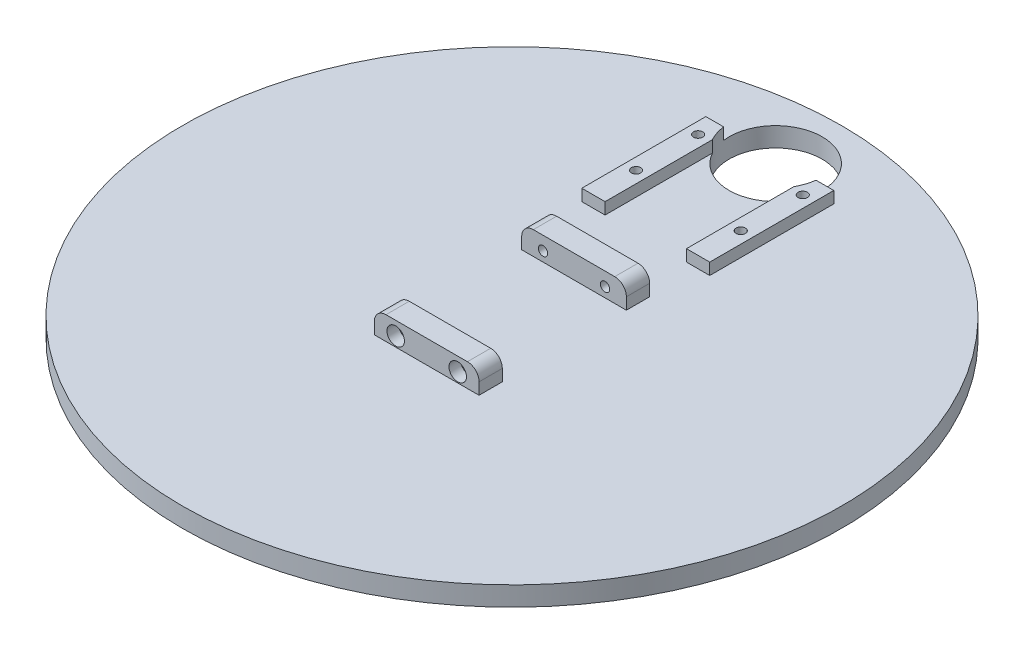
SolidWorks part; units mm, degrees
ref_plane "Front Plane" through (0, 0, 0) normal (0, 0, 1) x (1, 0, 0)
ref_plane "Top Plane" through (0, 0, 0) normal (0, 1, 0) x (1, 0, 0)
ref_plane "Right Plane" through (0, 0, 0) normal (1, 0, 0) x (0, 0, -1)
sketch "Sketch1" plane through (0, 0, 0) normal (0, 1, 0) x (1, 0, 0)
  circle A0 centre (0, 0) radius 32.65
  circle A1 centre (0, 0) radius 37.65
  dimension "D1" = 65.3
  dimension "D2" = 5
extrude "Boss-Extrude1" add sketch "Sketch1" along normal blind 10
sketch "Sketch2" plane through (0, 10, 0) normal (0, 1, 0) x (1, 0, 0)
  circle A0 centre (0, 0) radius 29.65
  circle A1 centre (0, 0) radius 32.65 construction
  circle A2 centre (0, 0) radius 32.65
  dimension "D1" = 3
extrude "Boss-Extrude2" add sketch "Sketch2" against normal blind 4
sketch "Sketch3" plane through (0, 10, 0) normal (0, 1, 0) x (1, 0, 0)
  circle A0 centre (0, 0) radius 85
  dimension "D1" = 170
extrude "Boss-Extrude3" add sketch "Sketch3" along normal blind 5
sketch "Sketch4" plane through (0, 15, 0) normal (0, 1, 0) x (1, 0, 0)
  line L0 (0, 0) -> (-32.7045, 0) construction
  line L1 (-13.5, 16) -> (13.5, 16)
  line L2 (-13.5, 16) -> (-13.5, 22)
  line L3 (-13.5, 22) -> (13.5, 22)
  line L4 (13.5, 16) -> (13.5, 22)
  line L5 (0, 0) -> (0, 16) construction
  dimension "D1" = 6
  dimension "D2" = 32
  dimension "D3" = 27
extrude "Boss-Extrude4" add sketch "Sketch4" along normal blind 6
fillet "Fillet1" radius 3 2 edges at (-13.5, 21, -19) (13.5, 21, -19)
sketch "Sketch6" plane through (0, 0, -22) normal (0, 0, -1) x (-1, 0, 0)
  line L0 (0, 15) -> (0, 21) construction
  line L1 (-13.5, 15) -> (13.5, 15) construction
  line L2 (-10.5, 21) -> (10.5, 21) construction
  circle A0 centre (-8, 17.5) radius 2.25
  circle A1 centre (8, 17.5) radius 2.25
  dimension "D2" = 4.5
  dimension "D1" = 16
  dimension "D3" = 2.5
extrude "Cut-Extrude1" cut sketch "Sketch6" against normal blind 3
hole_wizard "CSK for M2 Countersunk Flat Head Screw1" positions "3DSketch1" profile "Sketch5" countersink size "M2" standard "ISO" end condition through all
sketch3d "3DSketch1"
  line L8 (8, 17.5, -19) -> (8, 17.5, -22) construction
  line L9 (-8, 17.5, -19) -> (-8, 17.5, -22) construction
  point P21 (8, 17.5, -19)
  point P25 (-8, 17.5, -19)
sketch "Sketch5" plane through (8, 17.5, -19) normal (1, 0, 0) x (0, 1, 0)
  line L0 (0, 0) -> (0, 104)
  line L1 (0, 104) -> (1.2, 104)
  line L2 (1.2, 104) -> (1.2, 1)
  line L3 (1.2, 1) -> (2.2, 0)
  line L5 (2.2, 0) -> (0, 0)
  line L6 (-1.2, 1) -> (-2.2, 0) construction
  line L11 (0, -6.35) -> (0, 107.95) construction
  dimension "Thru Hole Dia." = 2.4
  dimension "Thru Hole Depth" = 104
  dimension "Near C'Sink Dia." = 4.4
  dimension "Near C'Sink Angle" = 90
mirror "Mirror1" about plane through (0, 0, 0) normal (0, 0, 1) of "CSK for M2 Countersunk Flat Head Screw1", "Fillet1", "Boss-Extrude4", "Cut-Extrude1"
sketch "Sketch8" plane through (0, 10, 0) normal (0, -1, 0) x (-1, 0, 0)
  line L0 (0, 85) -> (0, 22) construction
  line L1 (-5.75, 22) -> (-10.25, 22) construction
  circle A0 centre (0, 0) radius 85 construction
  circle A2 centre (13.5, 61.5) radius 2.25
  point P9 (0, 0)
  dimension "D2" = 4.5
  dimension "D1" = 39.5
  dimension "D3" = 27
extrude "Cut-Extrude2" cut sketch "Sketch8" against normal blind 5
sketch "Sketch11" plane through (0, 15, 0) normal (0, 1, 0) x (1, 0, 0)
  line L0 (-13.5, 61.5) -> (-13.5, 66.5) construction
  line L1 (-16.5, 66.5) -> (-10.5, 66.5)
  line L2 (-16.5, 66.5) -> (-16.5, 50.5)
  line L3 (-16.5, 50.5) -> (-10.5, 50.5)
  line L4 (-10.5, 66.5) -> (-10.5, 50.5)
  dimension "D1" = 5
  dimension "D2" = 16
  dimension "D3" = 6
extrude "Boss-Extrude5" add sketch "Sketch11" along normal blind 3
hole_wizard "CSK for M2 Countersunk Flat Head Screw2" positions "3DSketch2" profile "Sketch9" countersink size "M2" standard "ISO" end condition through all
sketch3d "3DSketch2"
  line L0 (-13.5, 15, -61.5) -> (-13.5, 10, -61.5) construction
  point P7 (-13.5, 15, -61.5)
sketch "Sketch9" plane through (-13.5, 15, -61.5) normal (1, 0, 0) x (0, 0, -1)
  line L0 (0, 0) -> (0, 6)
  line L1 (0, 6) -> (1.2, 6)
  line L2 (1.2, 6) -> (1.2, 1)
  line L3 (1.2, 1) -> (2.2, 0)
  line L5 (2.2, 0) -> (0, 0)
  line L6 (-1.2, 1) -> (-2.2, 0) construction
  line L11 (0, -6.35) -> (0, 107.95) construction
  dimension "Thru Hole Dia." = 2.4
  dimension "Thru Hole Depth" = 6
  dimension "Near C'Sink Dia." = 4.4
  dimension "Near C'Sink Angle" = 90
mirror "Mirror2" about plane through (0, 0, 0) normal (1, 0, 0) of "Boss-Extrude5", "CSK for M2 Countersunk Flat Head Screw2", "Cut-Extrude2"
pattern_linear "LPattern1" count 2 spacing 16 along (0, 0, 1) of "Mirror2", "Cut-Extrude2", "Boss-Extrude5", "CSK for M2 Countersunk Flat Head Screw2"
sketch "Sketch12" plane through (0, 15, 0) normal (0, 1, 0) x (1, 0, 0)
  line L0 (0, 68) -> (0, 22) construction
  line L1 (13.5, 22) -> (-13.5, 22) construction
  circle A0 centre (0, 68) radius 12
  point P2 (0, 69.249)
  dimension "D1" = 46
  dimension "24" = 24
extrude "Cut-Extrude3" cut sketch "Sketch12" against normal through all and the other way through all
